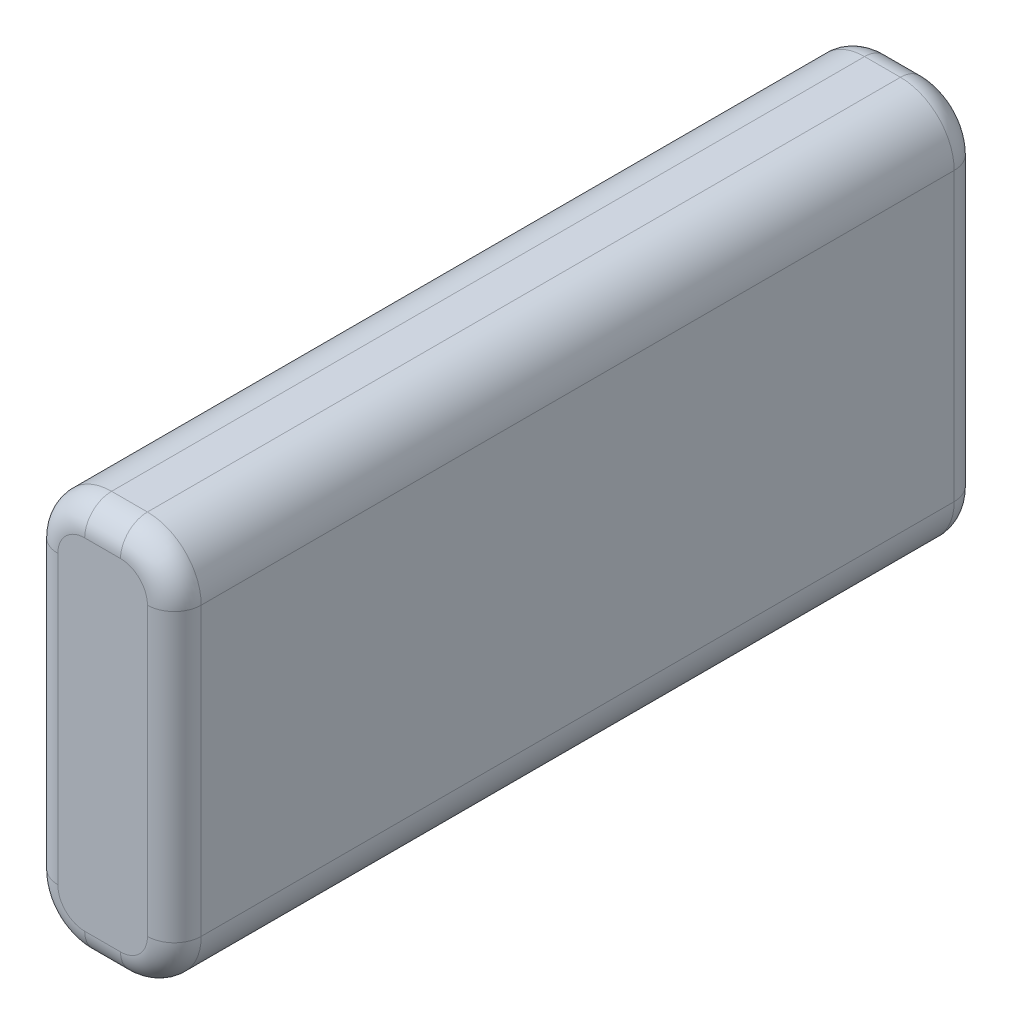
SolidWorks part; units mm, degrees
material "EPDM"
ref_plane "Front Plane" through (0, 0, 0) normal (0, 0, 1) x (1, 0, 0)
ref_plane "Top Plane" through (0, 0, 0) normal (0, 1, 0) x (1, 0, 0)
ref_plane "Right Plane" through (0, 0, 0) normal (1, 0, 0) x (0, 0, -1)
sketch "Block sketch 1" plane through (0, 0, 0) normal (0, 0, 1) x (1, 0, 0)
  line L0 (-2, -22) -> (2, -22)
  line L1 (8, -16) -> (8, 16)
  line L2 (2, 22) -> (-2, 22)
  line L3 (-8, 16) -> (-8, -16)
  arc A0 (2, -22) -> (8, -16) centre (2, -16) ccw
  arc A1 (8, 16) -> (2, 22) centre (2, 16) ccw
  arc A2 (-2, 22) -> (-8, 16) centre (-2, 16) ccw
  arc A3 (-8, -16) -> (-2, -22) centre (-2, -16) ccw
  dimension "D1" = 6
  dimension "D2" = 16
  dimension "D3" = 44
extrude "Block 1" add sketch "Block sketch 1" along normal blind 90 from offset 45 separate body
fillet "Block edge fillet 1" radius 3 16 edges at (-6.2426, -20.2426, 45) (-6.2426, 20.2426, 45) (6.2426, 20.2426, 45) (6.2426, -20.2426, 45) (6.2426, 20.2426, -45) (6.2426, -20.2426, -45) (0, -22, -45) (-6.2426, -20.2426, -45) (-8, 0, -45) (-6.2426, 20.2426, -45) (8, 0, 45) (-8, 0, 45) (0, 22, 45) (0, -22, 45) (8, 0, -45) (0, 22, -45)
